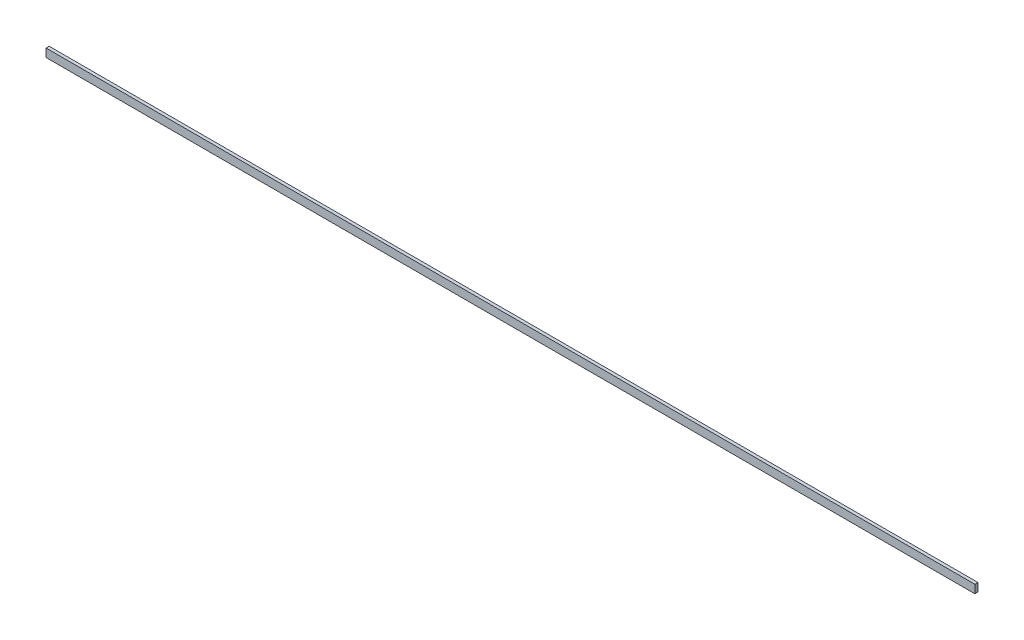
SolidWorks part; units mm, degrees
ref_plane "Front Plane" through (0, 0, 0) normal (0, 0, 1) x (1, 0, 0)
ref_plane "Top Plane" through (0, 0, 0) normal (0, 1, 0) x (1, 0, 0)
ref_plane "Right Plane" through (0, 0, 0) normal (1, 0, 0) x (0, 0, -1)
sketch "Sketch2" plane through (0, 0, 0) normal (0, 0, 1) x (1, 0, 0)
  line L1 (-450, -4) -> (450, -4)
  line L2 (-450, -4) -> (-450, 4)
  line L3 (-450, 4) -> (450, 4)
  line L4 (450, -4) -> (450, 4)
  line L5 (-450, -4) -> (450, 4) construction
  line L6 (-450, 4) -> (450, -4) construction
  point P0 (0, 0)
  dimension "D1" = 900
  dimension "D2" = 8
extrude "Boss-Extrude1" add sketch "Sketch2" along normal mid plane 3
